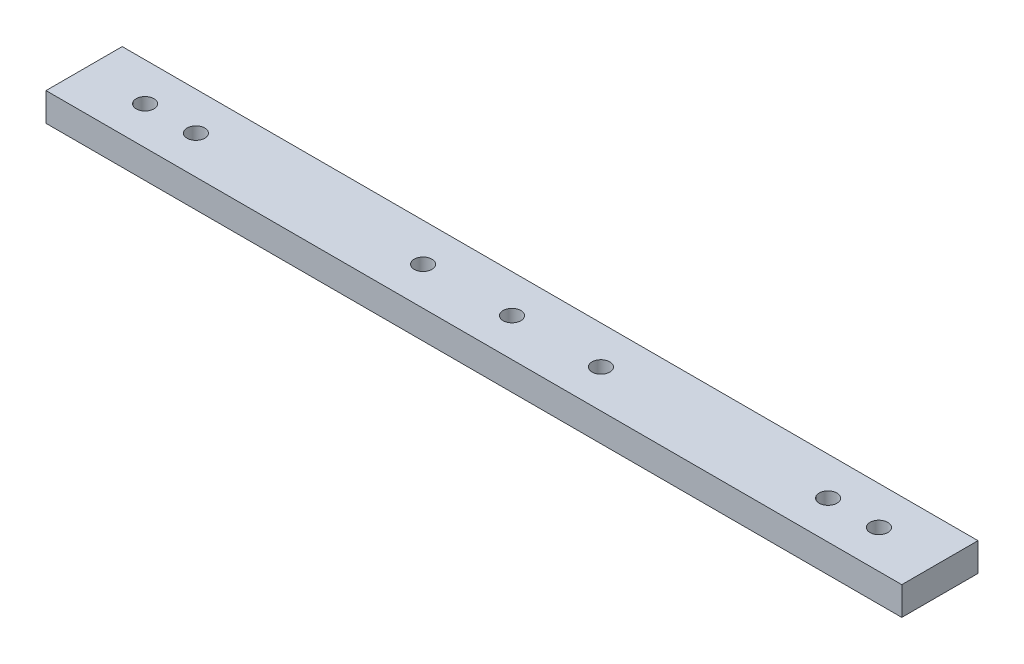
SolidWorks part; units mm, degrees
ref_plane "Front Plane" through (0, 0, 0) normal (0, 0, 1) x (1, 0, 0)
ref_plane "Top Plane" through (0, 0, 0) normal (0, 1, 0) x (1, 0, 0)
ref_plane "Right Plane" through (0, 0, 0) normal (1, 0, 0) x (0, 0, -1)
sketch "Sketch1" plane through (0, 0, 0) normal (0, 1, 0) x (1, 0, 0)
  line L1 (-71.3549, -2.9708) -> (97.0571, -2.9708)
  line L2 (-71.3549, -2.9708) -> (-71.3549, 12.0292)
  line L3 (-71.3549, 12.0292) -> (97.0571, 12.0292)
  line L4 (97.0571, -2.9708) -> (97.0571, 12.0292)
  dimension "D1" = 168.412
  dimension "D2" = 15
extrude "Boss-Extrude1" add sketch "Sketch1" along normal blind 5.588
sketch "Sketch2" plane through (0, 5.588, 0) normal (0, 1, 0) x (1, 0, 0)
  line L0 (-71.3549, 4.5292) -> (97.0571, 4.5292) construction
  line L1 (-71.3549, 12.0292) -> (-71.3549, -2.9708) construction
  line L2 (97.0571, -2.9708) -> (97.0571, 12.0292) construction
  line L3 (12.8511, -2.9708) -> (12.8511, 12.0292) construction
  line L4 (-71.3549, -2.9708) -> (97.0571, -2.9708) construction
  line L5 (97.0571, 12.0292) -> (-71.3549, 12.0292) construction
  circle A0 centre (-59.3549, 4.5292) radius 1.75
  circle A1 centre (-49.3549, 4.5292) radius 1.75
  circle A2 centre (75.0571, 4.5292) radius 1.75
  circle A3 centre (85.0571, 4.5292) radius 1.75
  dimension "D1" = 3.5
  dimension "D2" = 10
  dimension "D3" = 12
extrude "Cut-Extrude1" cut sketch "Sketch2" against normal through all
sketch "Sketch3" plane through (0, 5.588, 0) normal (0, 1, 0) x (1, 0, 0)
  line L0 (-71.3549, 4.5292) -> (97.0571, 4.5292) construction
  line L1 (-71.3549, 12.0292) -> (-71.3549, -2.9708) construction
  line L2 (97.0571, -2.9708) -> (97.0571, 12.0292) construction
  line L3 (12.8511, -2.9708) -> (12.8511, 12.0292) construction
  line L4 (-71.3549, -2.9708) -> (97.0571, -2.9708) construction
  line L5 (97.0571, 12.0292) -> (-71.3549, 12.0292) construction
  circle A0 centre (-4.6489, 4.5292) radius 1.75
  circle A1 centre (30.3511, 4.5292) radius 1.75
  circle A2 centre (12.8511, 4.5292) radius 1.75
  dimension "D1" = 3.5
  dimension "D2" = 35
extrude "Cut-Extrude2" cut sketch "Sketch3" against normal through all
